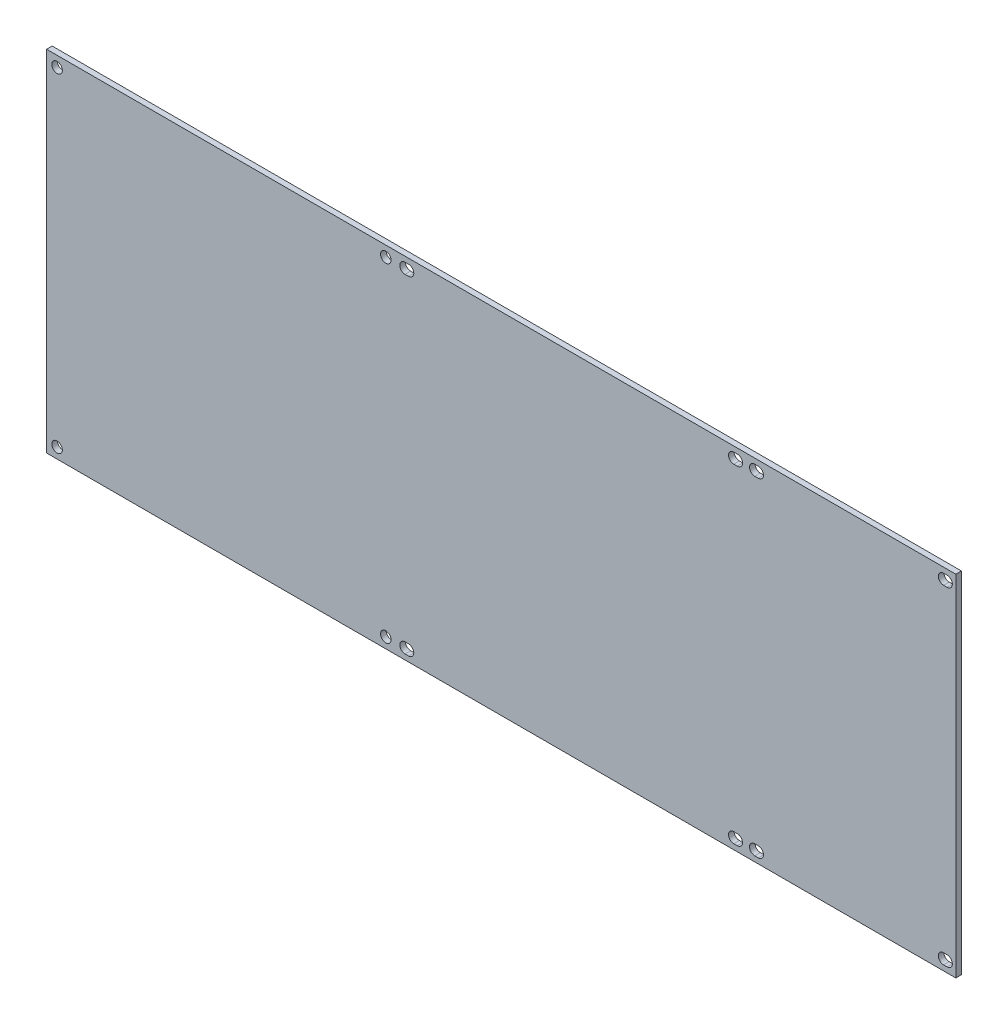
SolidWorks part; units mm, degrees
ref_plane "前视基准面" through (0, 0, 0) normal (0, 0, 1) x (1, 0, 0)
ref_plane "上视基准面" through (0, 0, 0) normal (0, 1, 0) x (1, 0, 0)
ref_plane "右视基准面" through (0, 0, 0) normal (1, 0, 0) x (0, 0, -1)
sketch "草图1" plane through (0, 0, 0) normal (0, 0, 1) x (1, 0, 0)
  line L0 (102.5, 97) -> (103.5, 97) construction
  line L1 (0, 0) -> (260, 0)
  line L2 (0, 0) -> (0, 100)
  line L3 (0, 100) -> (260, 100)
  line L4 (260, 0) -> (260, 100)
  line L5 (102.5, 98.5) -> (103.5, 98.5)
  line L6 (102.5, 95.5) -> (103.5, 95.5)
  line L7 (102.5, 3) -> (103.5, 3) construction
  line L8 (102.5, 4.5) -> (103.5, 4.5)
  line L9 (102.5, 1.5) -> (103.5, 1.5)
  line L10 (196.5, 97) -> (197.5, 97) construction
  line L11 (196.5, 98.5) -> (197.5, 98.5)
  line L12 (196.5, 95.5) -> (197.5, 95.5)
  line L13 (196.5, 3) -> (197.5, 3) construction
  line L14 (196.5, 4.5) -> (197.5, 4.5)
  line L15 (196.5, 1.5) -> (197.5, 1.5)
  line L16 (202.5, 3) -> (203.5, 3) construction
  line L17 (202.5, 4.5) -> (203.5, 4.5)
  line L18 (202.5, 1.5) -> (203.5, 1.5)
  line L19 (202.5, 97) -> (203.5, 97) construction
  line L20 (202.5, 98.5) -> (203.5, 98.5)
  line L21 (202.5, 95.5) -> (203.5, 95.5)
  line L22 (257.5, 97) -> (256.5, 97) construction
  line L23 (257.5, 95.5) -> (256.5, 95.5)
  line L24 (257.5, 98.5) -> (256.5, 98.5)
  line L25 (257.5, 3) -> (256.5, 3) construction
  line L26 (257.5, 1.5) -> (256.5, 1.5)
  line L27 (257.5, 4.5) -> (256.5, 4.5)
  circle A0 centre (3, 3) radius 1.5
  circle A3 centre (3, 97) radius 1.5
  circle A4 centre (97, 97) radius 1.5
  circle A5 centre (97, 3) radius 1.5
  arc A7 (102.5, 98.5) -> (102.5, 95.5) centre (102.5, 97) ccw
  arc A8 (103.5, 95.5) -> (103.5, 98.5) centre (103.5, 97) ccw
  arc A9 (102.5, 4.5) -> (102.5, 1.5) centre (102.5, 3) ccw
  arc A10 (103.5, 1.5) -> (103.5, 4.5) centre (103.5, 3) ccw
  arc A11 (196.5, 98.5) -> (196.5, 95.5) centre (196.5, 97) ccw
  arc A12 (197.5, 95.5) -> (197.5, 98.5) centre (197.5, 97) ccw
  arc A13 (196.5, 4.5) -> (196.5, 1.5) centre (196.5, 3) ccw
  arc A14 (197.5, 1.5) -> (197.5, 4.5) centre (197.5, 3) ccw
  arc A15 (202.5, 4.5) -> (202.5, 1.5) centre (202.5, 3) ccw
  arc A16 (203.5, 1.5) -> (203.5, 4.5) centre (203.5, 3) ccw
  arc A17 (202.5, 98.5) -> (202.5, 95.5) centre (202.5, 97) ccw
  arc A18 (203.5, 95.5) -> (203.5, 98.5) centre (203.5, 97) ccw
  arc A19 (257.5, 95.5) -> (257.5, 98.5) centre (257.5, 97) ccw
  arc A20 (256.5, 98.5) -> (256.5, 95.5) centre (256.5, 97) ccw
  arc A21 (257.5, 1.5) -> (257.5, 4.5) centre (257.5, 3) ccw
  arc A22 (256.5, 4.5) -> (256.5, 1.5) centre (256.5, 3) ccw
  point P19 (103, 97)
  point P26 (103, 3)
  point P31 (257, 97)
  point P36 (197, 97)
  point P43 (197, 3)
  point P52 (203, 3)
  point P59 (203, 97)
  point P64 (257, 3)
  dimension "D3" = 3
  dimension "D6" = 3
  dimension "D9" = 1
  dimension "D14" = 3
  dimension "D17" = 3
  dimension "D28" = 3
  dimension "D1" = 260
  dimension "D2" = 100
  dimension "D4" = 3
  dimension "D5" = 3
  dimension "D7" = 3
  dimension "D8" = 3
  dimension "D10" = 3
  dimension "D11" = 3
  dimension "D12" = 1
  dimension "D13" = 3
  dimension "D15" = 3
  dimension "D16" = 94
  dimension "D18" = 3
  dimension "D19" = 94
  dimension "D20" = 3
  dimension "D21" = 3
  dimension "D22" = 6
  dimension "D23" = 1
  dimension "D24" = 6
  dimension "D25" = 3
  dimension "D26" = 3
  dimension "D27" = 1
  dimension "D29" = 3
  dimension "D30" = 1
  dimension "D31" = 3
  dimension "D32" = 94
  dimension "D33" = 1
  dimension "D34" = 3
  dimension "D35" = 3
  dimension "D36" = 94
  dimension "D37" = 3
  dimension "D38" = 1
  dimension "D39" = 3
  dimension "D40" = 6
  dimension "D41" = 1
  dimension "D42" = 3
  dimension "D43" = 3
  dimension "D44" = 6
  dimension "D45" = 3
  dimension "D46" = 3
extrude "凸台-拉伸1" add sketch "草图1" along normal blind 1.6
